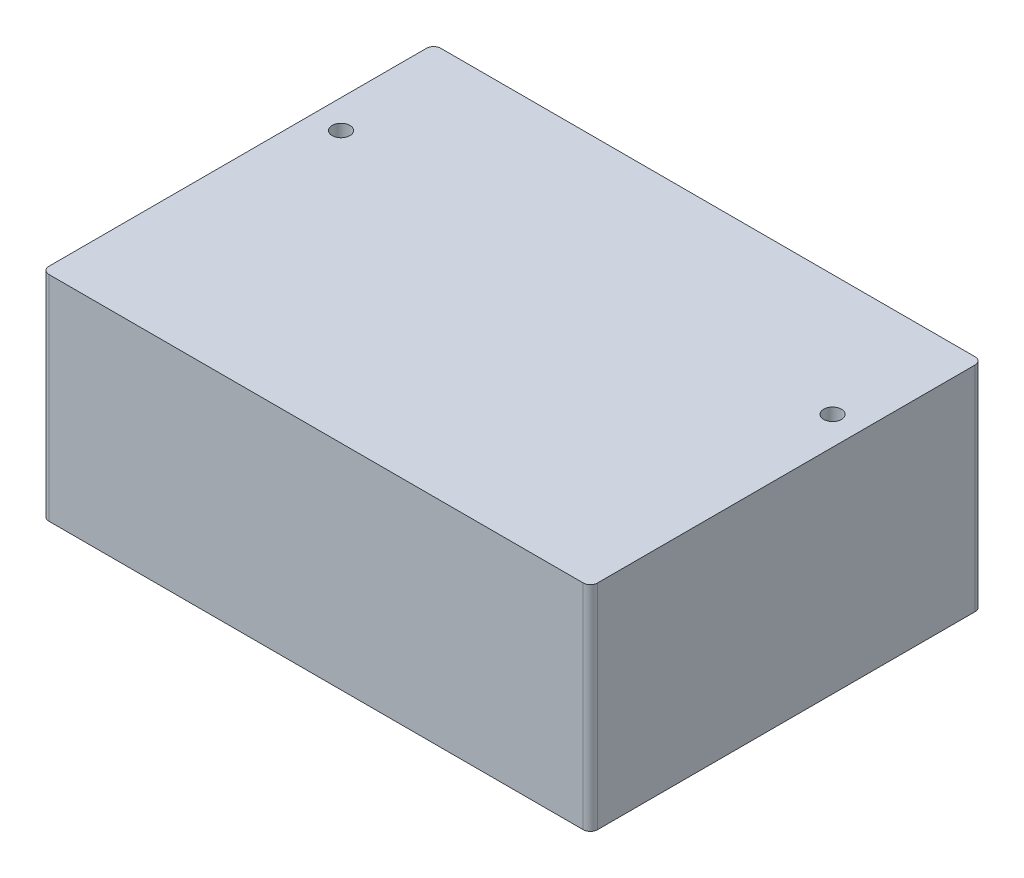
SolidWorks part; units mm, degrees
material "PBT General Purpose"
ref_plane "Front Plane" through (0, 0, 0) normal (0, 0, 1) x (1, 0, 0)
ref_plane "Top Plane" through (0, 0, 0) normal (0, 1, 0) x (1, 0, 0)
ref_plane "Right Plane" through (0, 0, 0) normal (1, 0, 0) x (0, 0, -1)
sketch "Sketch1" plane through (0, 0, 0) normal (0, 1, 0) x (1, 0, 0)
  line L1 (0, 0) -> (77, 0)
  line L2 (0, 0) -> (0, 60)
  line L3 (0, 60) -> (77, 60)
  line L4 (77, 0) -> (77, 60)
  dimension "D1" = 60
  dimension "D2" = 77
extrude "Boss-Extrude1" add sketch "Sketch1" along normal blind 30
fillet "Fillet1" radius 1 4 edges at (0, 15, -60) (77, 15, -60) (77, 15, 0) (0, 15, 0)
sketch "Sketch2" plane through (0, 30, 0) normal (0, 1, 0) x (1, 0, 0)
  line L0 (0, 55) -> (77, 55)
  line L1 (0, 59) -> (0, 1) construction
  line L2 (77, 1) -> (77, 59) construction
  line L3 (1, 0) -> (76, 0) construction
  line L4 (0, 55) -> (0, 60.0295)
  line L5 (0, 60.0295) -> (77, 60.0295)
  line L6 (77, 60.0295) -> (77, 55)
  dimension "D1" = 55
extrude "Cut-Extrude1" cut sketch "Sketch2" against normal blind 40
fillet "Fillet3" radius 1 2 edges at (0, 15, -55) (77, 15, -55)
sketch "Sketch5" plane through (0, 0, 0) normal (0, -1, 0) x (1, 0, 0)
  circle A0 centre (73, -17.5156) radius 1.25
extrude "Cut-Extrude4" cut sketch "Sketch5" against normal blind 5
cosmetic thread "Cosmetic Thread3" parameters "D1"=5, "D2"=3
sketch "Sketch6" plane through (0, 0, 0) normal (0, -1, 0) x (1, 0, 0)
  circle A0 centre (4, -17.5156) radius 1.25
extrude "Cut-Extrude5" cut sketch "Sketch6" against normal blind 5
cosmetic thread "Cosmetic Thread4" parameters "D1"=5, "D2"=3
sketch "Sketch7" plane through (0, 30, 0) normal (0, 1, 0) x (1, 0, 0)
  circle A0 centre (73, 38) radius 1.25
  circle A1 centre (4, 38) radius 1.25
extrude "Cut-Extrude6" cut sketch "Sketch7" against normal blind 5
cosmetic thread "Cosmetic Thread5" parameters "D2"=3
cosmetic thread "Cosmetic Thread6" parameters "D2"=3
